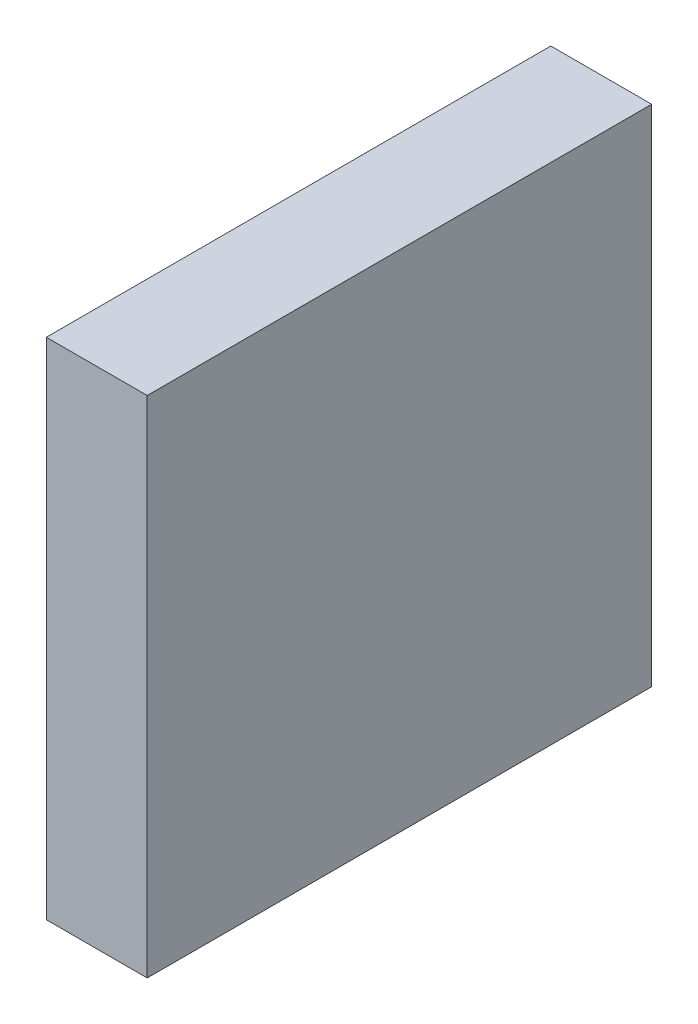
SolidWorks part; units mm, degrees
ref_plane "Front Plane" through (0, 0, 0) normal (0, 0, 1) x (1, 0, 0)
ref_plane "Top Plane" through (0, 0, 0) normal (0, 1, 0) x (1, 0, 0)
ref_plane "Right Plane" through (0, 0, 0) normal (1, 0, 0) x (0, 0, -1)
sketch "Sketch1" plane through (0, 0, 0) normal (0, 0, 1) x (1, 0, 0)
  line L1 (0, 0) -> (1, 0)
  line L2 (0, 0) -> (0, 5)
  line L3 (0, 5) -> (1, 5)
  line L4 (1, 0) -> (1, 5)
  dimension "D1" = 5
  dimension "D2" = 1
extrude "Boss-Extrude1" add sketch "Sketch1" along normal blind 5
